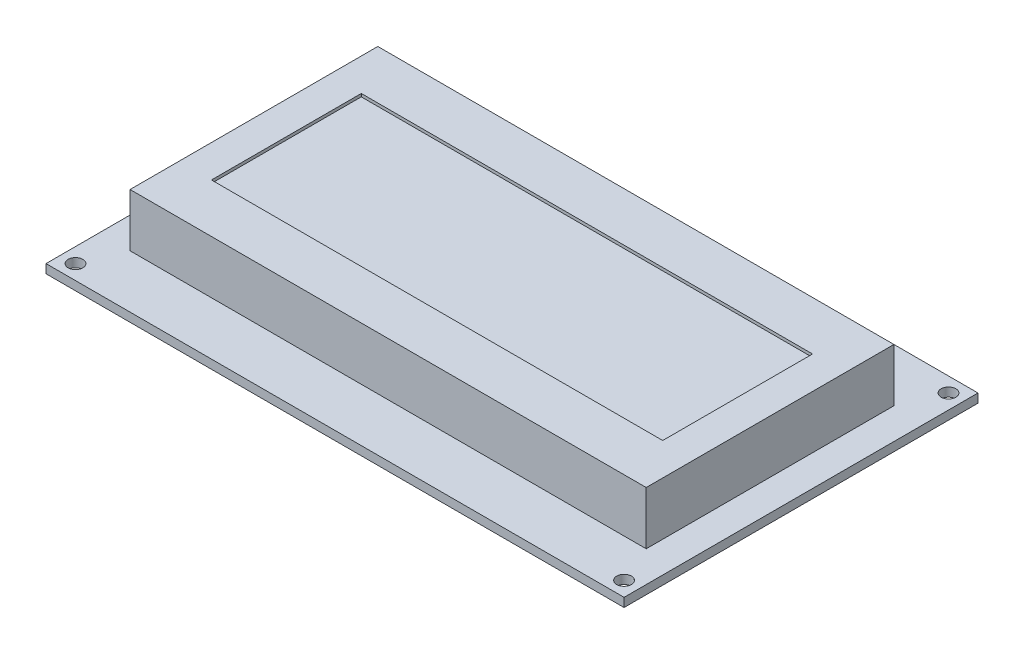
SolidWorks part; units mm, degrees
ref_plane "Front Plane" through (0, 0, 0) normal (0, 0, 1) x (1, 0, 0)
ref_plane "Top Plane" through (0, 0, 0) normal (0, 1, 0) x (1, 0, 0)
ref_plane "Right Plane" through (0, 0, 0) normal (1, 0, 0) x (0, 0, -1)
sketch "Sketch1" plane through (0, 0, 0) normal (0, 1, 0) x (1, 0, 0)
  line L1 (0, 0) -> (98, 0)
  line L2 (0, 0) -> (0, 60)
  line L3 (0, 60) -> (98, 60)
  line L4 (98, 0) -> (98, 60)
  dimension "D1" = 98
  dimension "D2" = 60
extrude "Boss-Extrude1" add sketch "Sketch1" along normal blind 1.5
sketch "Sketch2" plane through (0, 1.5, 0) normal (0, 1, 0) x (1, 0, 0)
  line L0 (0, 60) -> (98, 0) construction
  line L1 (0, 0) -> (98, 60) construction
  line L3 (5.25, 9) -> (92.75, 9)
  line L4 (5.25, 9) -> (5.25, 51)
  line L5 (5.25, 51) -> (92.75, 51)
  line L6 (92.75, 9) -> (92.75, 51)
  line L7 (5.25, 9) -> (92.75, 51) construction
  line L8 (5.25, 51) -> (92.75, 9) construction
  point P8 (49, 30)
  dimension "D1" = 42
  dimension "D2" = 87.5
extrude "Boss-Extrude2" add sketch "Sketch2" along normal blind 9
sketch "Sketch3" plane through (0, 10.5, 0) normal (0, 1, 0) x (1, 0, 0)
  line L0 (92.75, 51) -> (5.25, 51) construction
  line L1 (10.75, 42.7) -> (87.25, 42.7)
  line L2 (10.75, 42.7) -> (10.75, 17.3)
  line L3 (10.75, 17.3) -> (87.25, 17.3)
  line L4 (87.25, 42.7) -> (87.25, 17.3)
  line L5 (10.75, 42.7) -> (87.25, 17.3) construction
  line L6 (10.75, 17.3) -> (87.25, 42.7) construction
  line L7 (49, 51) -> (49, 30) construction
  line L8 (49, 30) -> (5.25, 30) construction
  line L9 (5.25, 51) -> (5.25, 9) construction
  line L10 (5.25, 51) -> (5.25, 9) construction
  point P0 (49, 30)
  dimension "D1" = 8.3
  dimension "D2" = 5.5
extrude "Cut-Extrude1" cut sketch "Sketch3" against normal blind 0.5
sketch "Sketch4" plane through (0, 1.5, 0) normal (0, 1, 0) x (1, 0, 0)
  line L0 (5.25, 30) -> (49, 30) construction
  line L1 (95.5, 2.5) -> (2.5, 2.5) construction
  line L2 (95.5, 2.5) -> (95.5, 57.5) construction
  line L3 (95.5, 57.5) -> (2.5, 57.5) construction
  line L4 (2.5, 2.5) -> (2.5, 57.5) construction
  line L5 (95.5, 2.5) -> (2.5, 57.5) construction
  line L6 (95.5, 57.5) -> (2.5, 2.5) construction
  line L7 (5.25, 51) -> (5.25, 9) construction
  line L8 (49, 30) -> (49, 60) construction
  line L9 (98, 60) -> (0, 60) construction
  line L10 (0, 60) -> (0, 0) construction
  circle A0 centre (2.5, 57.5) radius 1.25
  circle A1 centre (95.5, 57.5) radius 1.25
  circle A2 centre (95.5, 2.5) radius 1.25
  circle A3 centre (2.5, 2.5) radius 1.25
  point P2 (49, 30)
  dimension "D1" = 2.5
  dimension "D2" = 2.5
  dimension "D3" = 2.5
  dimension "D4" = 2.5
  dimension "D5" = 2.5
  dimension "D6" = 2.5
extrude "Cut-Extrude2" cut sketch "Sketch4" against normal through all
sketch "Sketch5" plane through (0, 1.5, 0) normal (0, 1, 0) x (1, 0, 0)
  line L0 (0, 60) -> (0, 0) construction
  line L1 (98, 60) -> (0, 60) construction
  circle A0 centre (10, 57.5) radius 0.5
  circle A1 centre (12.54, 57.5) radius 0.5
  circle A2 centre (15.08, 57.5) radius 0.5
  circle A3 centre (20.16, 57.5) radius 0.5
  circle A4 centre (22.7, 57.5) radius 0.5
  circle A5 centre (25.24, 57.5) radius 0.5
  circle A6 centre (27.78, 57.5) radius 0.5
  circle A7 centre (30.32, 57.5) radius 0.5
  circle A8 centre (32.86, 57.5) radius 0.5
  dimension "D1" = 1
  dimension "D5" = 1
  dimension "D8" = 6
  dimension "D2" = 10
  dimension "D3" = 2.5
  dimension "D6" = 2.5
  dimension "D7" = 5.08
  dimension "D4" = 3
extrude "Cut-Extrude3" cut sketch "Sketch5" against normal blind 10
sketch "Sketch6" plane through (0, 1.5, 0) normal (0, 1, 0) x (1, 0, 0)
  line L0 (19.41, 58.25) -> (20.91, 58.25)
  line L1 (9.25, 58.25) -> (10.75, 58.25)
  line L2 (9.25, 58.25) -> (9.25, 56.75)
  line L3 (9.25, 56.75) -> (10.75, 56.75)
  line L4 (10.75, 58.25) -> (10.75, 56.75)
  line L5 (20.91, 58.25) -> (20.91, 56.75)
  line L6 (19.41, 56.75) -> (20.91, 56.75)
  line L7 (19.41, 58.25) -> (19.41, 56.75)
  circle A0 centre (12.54, 57.5) radius 0.75
  circle A1 centre (12.54, 57.5) radius 0.5
  circle A2 centre (15.08, 57.5) radius 0.75
  circle A3 centre (15.08, 57.5) radius 0.5
  circle A4 centre (22.7, 57.5) radius 0.75
  circle A5 centre (22.7, 57.5) radius 0.5
  circle A6 centre (25.24, 57.5) radius 0.75
  circle A7 centre (25.24, 57.5) radius 0.5
  circle A8 centre (27.78, 57.5) radius 0.75
  circle A9 centre (27.78, 57.5) radius 0.5
  circle A10 centre (30.32, 57.5) radius 0.75
  circle A11 centre (30.32, 57.5) radius 0.5
  circle A12 centre (32.86, 57.5) radius 0.75
  circle A13 centre (32.86, 57.5) radius 0.5
  circle A14 centre (10, 57.5) radius 0.5
  circle A15 centre (20.16, 57.5) radius 0.5
  dimension "D1" = 1.5
  dimension "D2" = 1
  dimension "D4" = 1.5
  dimension "D5" = 1
  dimension "D9" = 0.75
  dimension "D11" = 1
  dimension "D7" = 1.5
  dimension "D8" = 1.5
  dimension "D10" = 0.75
  dimension "D3" = 2
  dimension "D6" = 5
  dimension "D12" = 2
extrude "Boss-Extrude3" add sketch "Sketch6" along normal blind 0.1
sketch "Sketch7" plane through (0, 1.6, 0) normal (0, 1, 0) x (1, 0, 0)
  line L0 (9.25, 58.25) -> (9.25, 56.75)
  line L1 (9.25, 56.75) -> (10.75, 56.75)
  line L2 (10.75, 56.75) -> (10.75, 58.25)
  line L3 (10.75, 58.25) -> (9.25, 58.25)
  line L4 (19.41, 56.75) -> (20.91, 56.75)
  line L5 (20.91, 56.75) -> (20.91, 58.25)
  line L6 (20.91, 58.25) -> (19.41, 58.25)
  line L7 (19.41, 58.25) -> (19.41, 56.75)
  circle A0 centre (10, 57.5) radius 0.5
  circle A1 centre (12.54, 57.5) radius 0.5
  circle A2 centre (15.08, 57.5) radius 0.5
  circle A3 centre (12.54, 57.5) radius 0.75
  circle A4 centre (15.08, 57.5) radius 0.75
  circle A5 centre (20.16, 57.5) radius 0.5
  circle A6 centre (22.7, 57.5) radius 0.5
  circle A7 centre (22.7, 57.5) radius 0.75
  circle A8 centre (25.24, 57.5) radius 0.75
  circle A9 centre (25.24, 57.5) radius 0.5
  circle A10 centre (27.78, 57.5) radius 0.75
  circle A11 centre (27.78, 57.5) radius 0.5
  circle A12 centre (30.32, 57.5) radius 0.75
  circle A13 centre (30.32, 57.5) radius 0.5
  circle A14 centre (32.86, 57.5) radius 0.75
  circle A15 centre (32.86, 57.5) radius 0.5
  dimension "D1" = 1
  dimension "D3" = 5
  dimension "D2" = 3
extrude "Boss-Extrude4" add sketch "Sketch7" against normal blind 1.7
sketch "Sketch8" plane through (0, 0, 0) normal (0, -1, 0) x (1, 0, 0)
  line L0 (5.25, -9) -> (5.25, -12)
  line L1 (5.25, -51) -> (5.25, -9) construction
  line L2 (5.25, -9) -> (8.25, -9)
  line L3 (5.25, -9) -> (92.75, -9) construction
  line L4 (5.75, -9.5) -> (5.75, -12)
  line L5 (5.75, -9.5) -> (8.25, -9.5)
  line L6 (8.25, -9) -> (8.25, -9.5)
  line L7 (5.75, -12) -> (5.25, -12)
  line L8 (49, 5.399) -> (49, -68.7795) construction
  line L10 (0, -60) -> (0, 0) construction
  line L12 (92.25, -12) -> (92.75, -12)
  line L13 (89.75, -9) -> (89.75, -9.5)
  line L14 (92.25, -9.5) -> (89.75, -9.5)
  line L15 (92.25, -9.5) -> (92.25, -12)
  line L16 (92.75, -9) -> (89.75, -9)
  line L17 (92.75, -9) -> (92.75, -12)
  line L18 (-9.9178, -30) -> (103.4748, -30) construction
  line L19 (0, 0) -> (98, 0) construction
  line L21 (92.75, -51) -> (92.75, -48)
  line L22 (92.75, -51) -> (89.75, -51)
  line L23 (92.25, -50.5) -> (92.25, -48)
  line L24 (92.25, -50.5) -> (89.75, -50.5)
  line L25 (89.75, -51) -> (89.75, -50.5)
  line L26 (92.25, -48) -> (92.75, -48)
  line L27 (5.75, -48) -> (5.25, -48)
  line L28 (8.25, -51) -> (8.25, -50.5)
  line L29 (5.75, -50.5) -> (8.25, -50.5)
  line L30 (5.75, -50.5) -> (5.75, -48)
  line L31 (5.25, -51) -> (8.25, -51)
  line L32 (5.25, -51) -> (5.25, -48)
  dimension "D1" = 3
  dimension "D2" = 3
  dimension "D4" = 49
  dimension "D5" = 30
  dimension "D3" = 0.5
extrude "Boss-Extrude5" add sketch "Sketch8" along normal blind 2.59
equation "\"D4@Sketch4\" = \"D1@Sketch4\""
equation "\"D5@Sketch4\" = \"D1@Sketch4\""
equation "\"D6@Sketch4\" = \"D1@Sketch4\""
